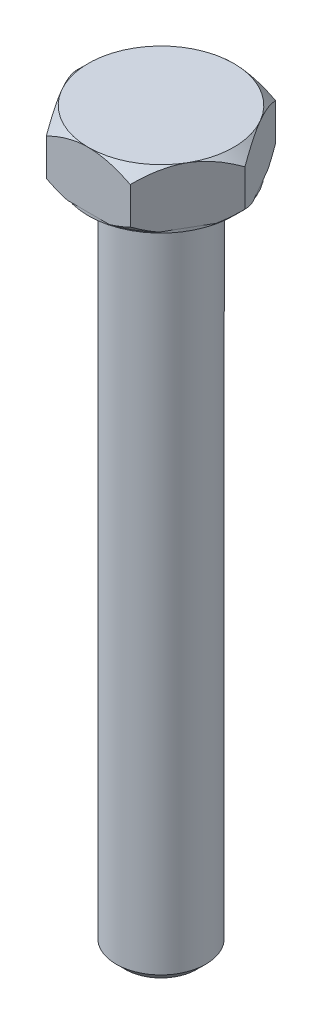
SolidWorks part; units mm, degrees
material "Cast Stainless Steel"
ref_plane "Front Plane" through (0, 0, 0) normal (0, 0, 1) x (1, 0, 0)
ref_plane "Top Plane" through (0, 0, 0) normal (0, 1, 0) x (1, 0, 0)
ref_plane "Right Plane" through (0, 0, 0) normal (1, 0, 0) x (0, 0, -1)
sketch "Sketch1" plane through (0, 0, 0) normal (0, 1, 0) x (1, 0, 0)
  line L0 (0, 0) -> (7.5056, 0) construction
  line L1 (7.5056, 0) -> (3.7528, 6.5)
  line L2 (3.7528, 6.5) -> (-3.7528, 6.5)
  line L3 (-3.7528, 6.5) -> (-7.5056, 0)
  line L4 (-7.5056, 0) -> (-3.7528, -6.5)
  line L5 (-3.7528, -6.5) -> (3.7528, -6.5)
  line L6 (3.7528, -6.5) -> (7.5056, 0)
  circle A0 centre (0, 0) radius 6.5 construction
  dimension "D1" = 13
extrude "Boss-Extrude1" add sketch "Sketch1" against normal blind 5.3
sketch "Sketch4" plane through (0, 0, 0) normal (1, 0, 0) x (0, 0, -1)
  line L0 (-6.5, 0) -> (-8.15, 0)
  line L1 (-8.15, 0) -> (-8.15, -1.65)
  line L2 (-8.15, -1.65) -> (-6.5, 0)
  line L3 (-6.5, -2.65) -> (6.5, -2.65) construction
  line L4 (-8.15, -3.65) -> (-6.5, -5.3)
  line L5 (-8.15, -5.3) -> (-8.15, -3.65)
  line L6 (-6.5, -5.3) -> (-8.15, -5.3)
  line L7 (0, 0) -> (0, -2.65) construction
  dimension "D1" = 45
  dimension "D2" = 2.65
  dimension "D3" = 1.65
  dimension "D4" = 13
revolve "Cut-Revolve1" cut sketch "Sketch4" angle 360 about L7
sketch "Sketch2" plane through (0, -5.3, 0) normal (0, -1, 0) x (1, 0, 0)
  circle A0 centre (0, 0) radius 6.5
  dimension "D1" = 13
extrude "Cut-Extrude1" cut sketch "Sketch2" against normal blind 0.265 flip side to cut
sketch "Sketch3" plane through (0, -5.3, 0) normal (0, -1, 0) x (1, 0, 0)
  circle A0 centre (0, 0) radius 4
  dimension "D1" = 8
extrude "Boss-Extrude2" add sketch "Sketch3" along normal blind 60
chamfer "Chamfer1" distance 0.8 angle 45 1 edges at (0, -65.3, -4)
equation "\"k\"= 5.3"
equation "\"e\"= 14.38"
equation "\"S\"= 13"
equation "\"L\" = 60"
equation "\"D1@Sketch1\"=\"S\""
equation "\"D1@Boss-Extrude1\"=\"k\""
equation "\"D1@Sketch2\"=\"S\""
equation "\"D1@Cut-Extrude1\"=\"k\"/20"
equation "\"d\"= 8"
equation "\"D1@Sketch3\"=\"d\""
equation "\"D1@Boss-Extrude2\"=\"L\""
equation "\"D2@Sketch4\"=\"k\"/2"
equation "\"D3@Sketch4\"=\"D2@Sketch4\"-1"
equation "\"D4@Sketch4\"=\"S\""
equation "\"D1@Chamfer1\"=\"d\"/10"
